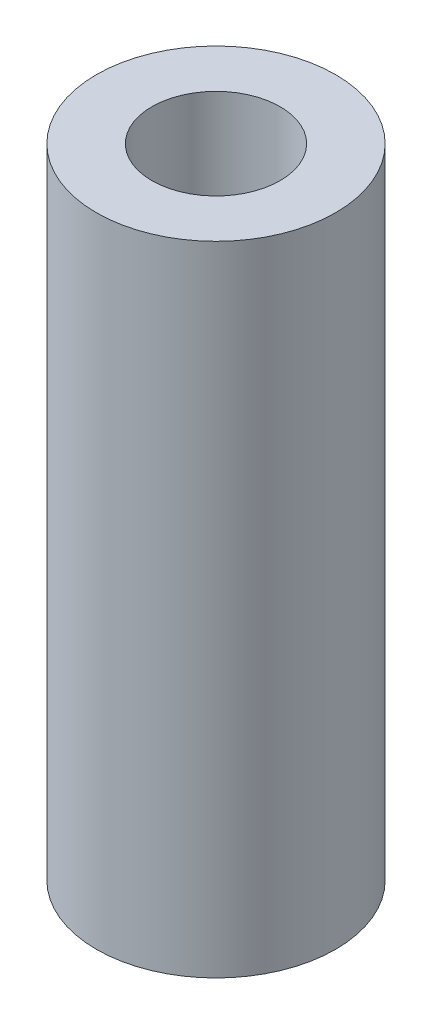
SolidWorks part; units mm, degrees
material "PET"
ref_plane "Front Plane" through (0, 0, 0) normal (0, 0, 1) x (1, 0, 0)
ref_plane "Top Plane" through (0, 0, 0) normal (0, 1, 0) x (1, 0, 0)
ref_plane "Right Plane" through (0, 0, 0) normal (1, 0, 0) x (0, 0, -1)
sketch "Sketch1" plane through (0, 0, 0) normal (0, 1, 0) x (1, 0, 0)
  circle A0 centre (0, 0) radius 2.5527
  circle A1 centre (0, 0) radius 4.7625
  dimension "D1" = 5.1054
  dimension "D2" = 9.525
extrude "Boss-Extrude1" add sketch "Sketch1" along normal blind 25.4
